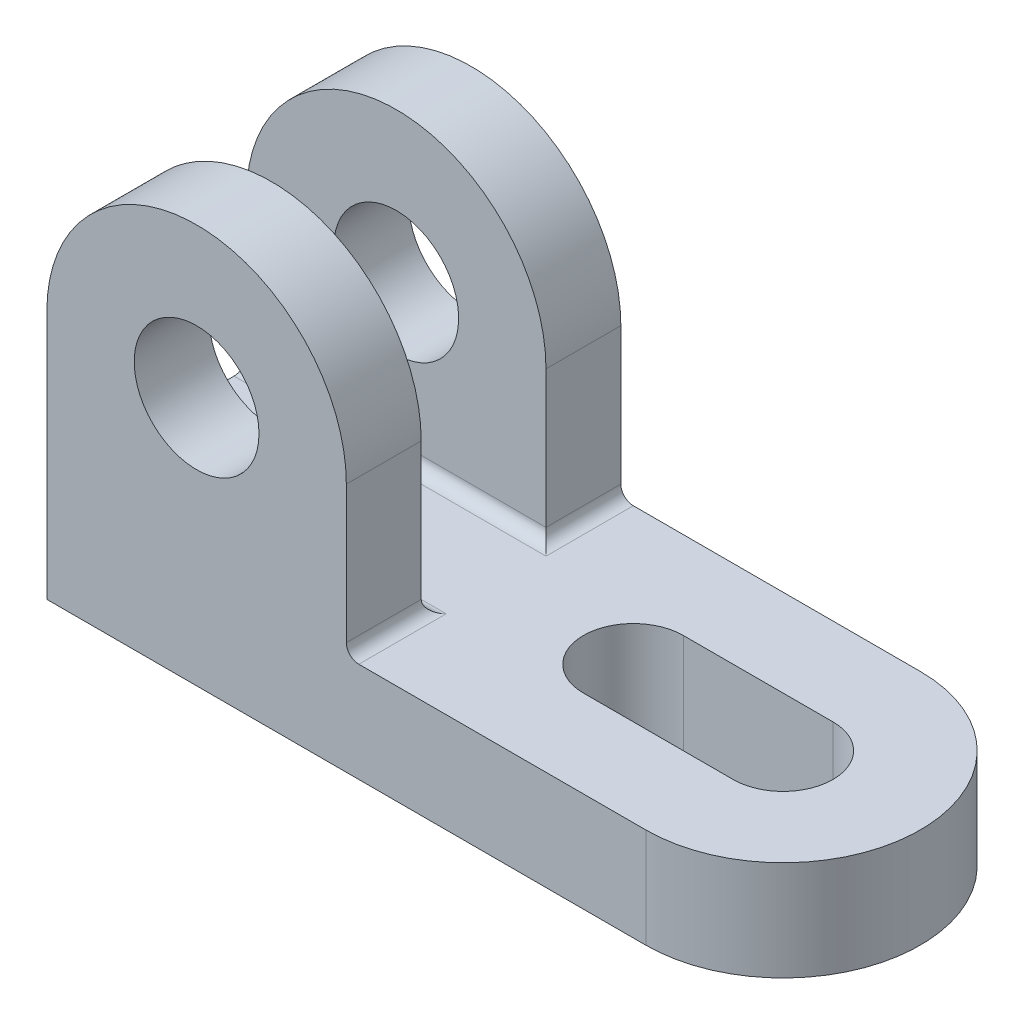
SolidWorks part; units mm, degrees
ref_plane "Front Plane" through (0, 0, 0) normal (0, 0, 1) x (1, 0, 0)
ref_plane "Top Plane" through (0, 0, 0) normal (0, 1, 0) x (1, 0, 0)
ref_plane "Right Plane" through (0, 0, 0) normal (1, 0, 0) x (0, 0, -1)
sketch "Sketch1" plane through (0, 0, 0) normal (0, 1, 0) x (1, 0, 0)
  line L0 (0, 0) -> (118, 0)
  line L1 (118, 0) -> (118, 44)
  line L2 (118, 44) -> (0, 44)
  line L3 (0, 44) -> (0, 0)
  circle A0 centre (96, 22) radius 22
  dimension "D1" = 118
  dimension "D2" = 44
extrude "Boss-Extrude3" add sketch "Sketch1" along normal blind 16 contours A0 L2 L3 L0 | A0
sketch "Sketch2" plane through (0, 16, 0) normal (0, 1, 0) x (1, 0, 0)
  line L0 (72, 22) -> (96, 22) construction
  line L1 (72, 30) -> (96, 30)
  line L2 (72, 14) -> (96, 14)
  line L3 (96, 44) -> (0, 44) construction
  line L4 (0, 44) -> (0, 0) construction
  arc A0 (72, 30) -> (72, 14) centre (72, 22) ccw
  arc A1 (96, 14) -> (96, 30) centre (96, 22) ccw
  point P2 (84, 22)
  point P14 (0, 22)
  dimension "D1" = 16
  dimension "D2" = 24
  dimension "D3" = 22
  dimension "D4" = 84
extrude "Cut-Extrude1" cut sketch "Sketch2" against normal through all
sketch "Sketch3" plane through (0, 0, 0) normal (0, 0, 1) x (1, 0, 0)
  line L1 (0, 16) -> (48, 16)
  line L2 (0, 16) -> (0, 40)
  line L3 (0, 40) -> (48, 40)
  line L4 (48, 16) -> (48, 40)
  circle A0 centre (24, 40) radius 24
extrude "Boss-Extrude5" add sketch "Sketch3" against normal blind 12 contours L4 L3 L2 L1 | A0
sketch "Sketch6" plane through (0, 0, 0) normal (0, 0, 1) x (1, 0, 0)
  circle A0 centre (24, 40) radius 10
extrude "Cut-Extrude3" cut sketch "Sketch6" against normal through all
ref_plane "Plane1" through (0, 0, -22) normal (0, 0, 1) x (1, 0, 0)
mirror "Mirror3" about plane through (0, 0, -22) normal (0, 0, 1) of "Cut-Extrude3", "Boss-Extrude5"
fillet "Fillet3" radius 2 4 edges at (48, 16, -38) (24, 16, -32) (24, 16, -12) (48, 16, -6)
